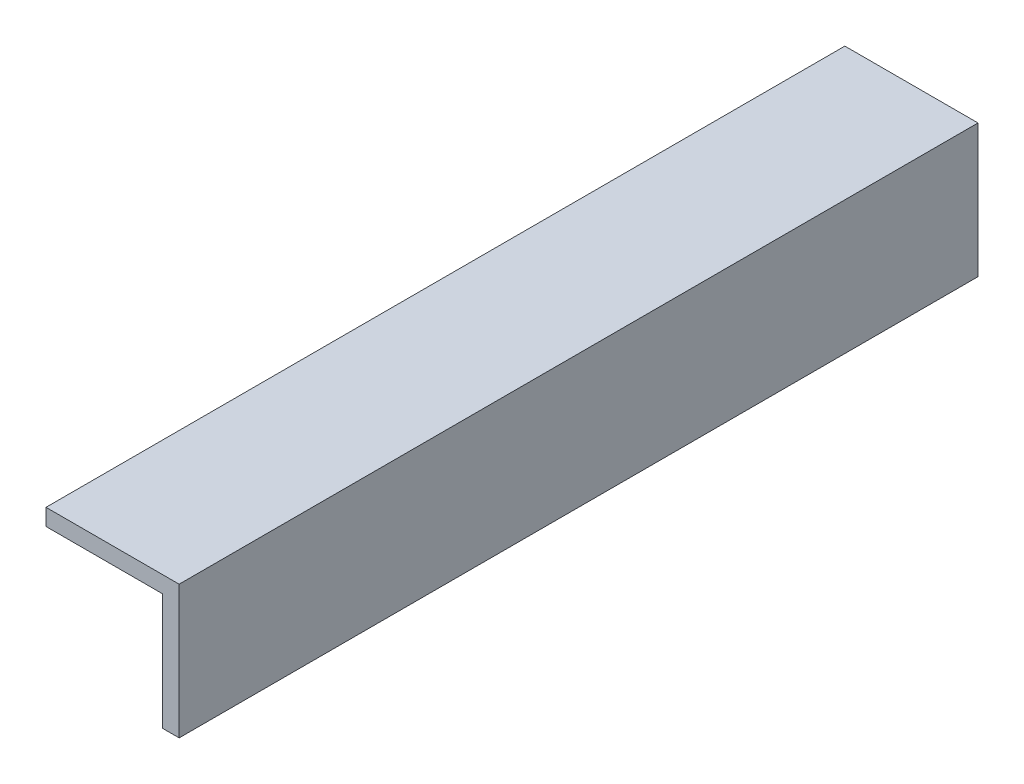
SolidWorks part; units mm, degrees
material "6061 Alloy"
ref_plane "Front Plane" through (0, 0, 0) normal (0, 0, 1) x (1, 0, 0)
ref_plane "Top Plane" through (0, 0, 0) normal (0, 1, 0) x (1, 0, 0)
ref_plane "Right Plane" through (0, 0, 0) normal (1, 0, 0) x (0, 0, -1)
sketch "Sketch1" plane through (0, 0, 0) normal (0, 0, 1) x (1, 0, 0)
  line L0 (0, 0) -> (25.4, 0)
  line L1 (25.4, 0) -> (25.4, -25.4)
  line L2 (0, 0) -> (0, -3.175)
  line L3 (25.4, -25.4) -> (22.225, -25.4)
  line L4 (22.225, -25.4) -> (22.225, -3.175)
  line L5 (22.225, -3.175) -> (0, -3.175)
extrude "Boss-Extrude1" add sketch "Sketch1" along normal blind 152.4 contours L0 L1 L3 L4 L5 L2
